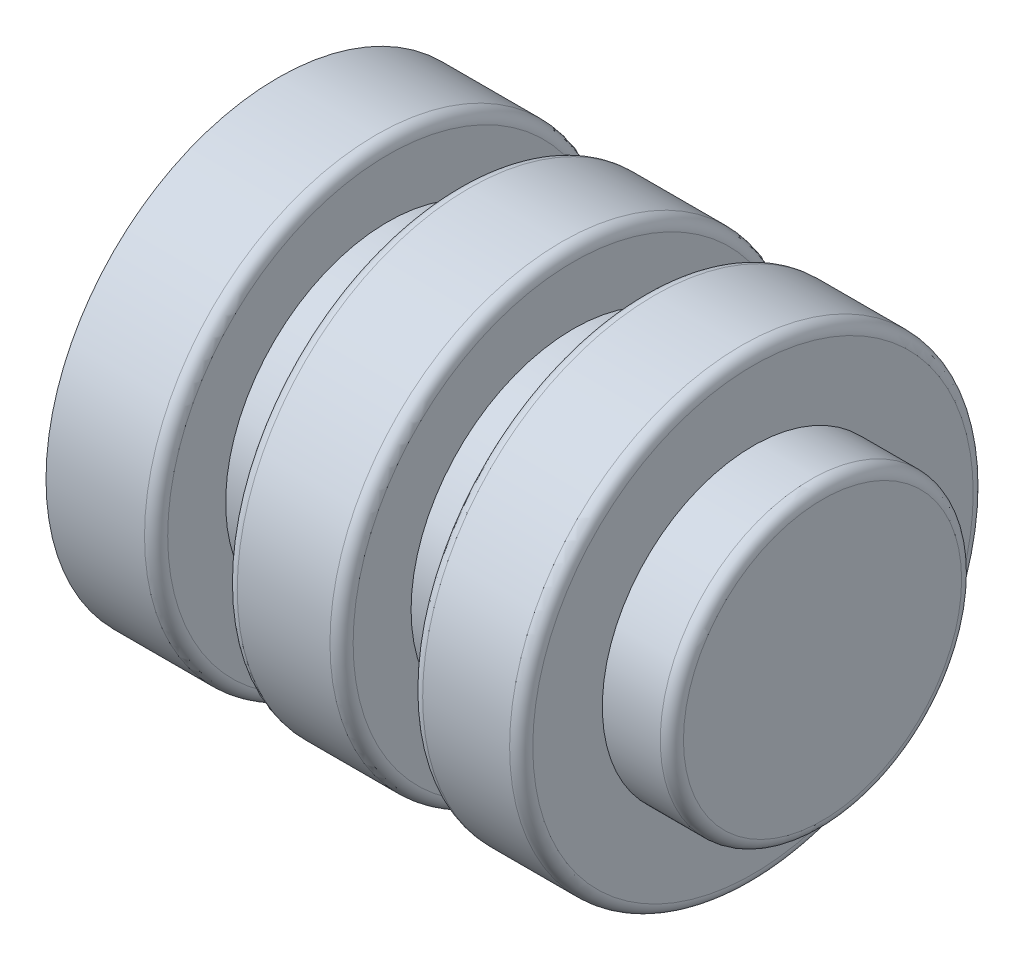
SolidWorks part; units mm, degrees
ref_plane "Front Plane" through (0, 0, 0) normal (0, 0, 1) x (1, 0, 0)
ref_plane "Top Plane" through (0, 0, 0) normal (0, 1, 0) x (1, 0, 0)
ref_plane "Right Plane" through (0, 0, 0) normal (1, 0, 0) x (0, 0, -1)
sketch "Sketch1" plane through (0, 0, 0) normal (1, 0, 0) x (0, 0, -1)
  circle A0 centre (0, 0) radius 10
  dimension "D1" = 20
extrude "Boss-Extrude1" add sketch "Sketch1" along normal blind 4.75
sketch "Sketch4" plane through (4.75, 0, 0) normal (1, 0, 0) x (0, 0, -1)
  circle A0 centre (0, 0) radius 6.5
  dimension "D1" = 13
extrude "Boss-Extrude2" add sketch "Sketch4" along normal blind 3
sketch "Sketch5" plane through (0, 0, 0) normal (-1, 0, 0) x (0, 0, 1)
  circle A0 centre (0, 0) radius 7
  dimension "D1" = 14
extrude "Boss-Extrude3" add sketch "Sketch5" along normal blind 3
fillet "Fillet1" radius 0.5 1 edges at (7.75, 0, -6.5)
sketch "Sketch6" plane through (-3, 0, 0) normal (-1, 0, 0) x (0, 0, 1)
  circle A0 centre (0, 0) radius 10
  dimension "D1" = 20
extrude "Boss-Extrude4" add sketch "Sketch6" along normal blind 5
sketch "Sketch7" plane through (-8, 0, 0) normal (-1, 0, 0) x (0, 0, 1)
  circle A0 centre (0, 0) radius 7
  dimension "D1" = 14
extrude "Boss-Extrude5" add sketch "Sketch7" along normal blind 3
sketch "Sketch9" plane through (-11, 0, 0) normal (-1, 0, 0) x (0, 0, 1)
  circle A0 centre (0, 0) radius 10
  dimension "D1" = 20
extrude "Boss-Extrude6" add sketch "Sketch9" along normal blind 4.75
fillet "Fillet2" radius 0.5 5 edges at (-11, 0, 10) (-8, 0, 10) (-3, 0, 10) (0, 0, -10) (4.75, 0, -10)
